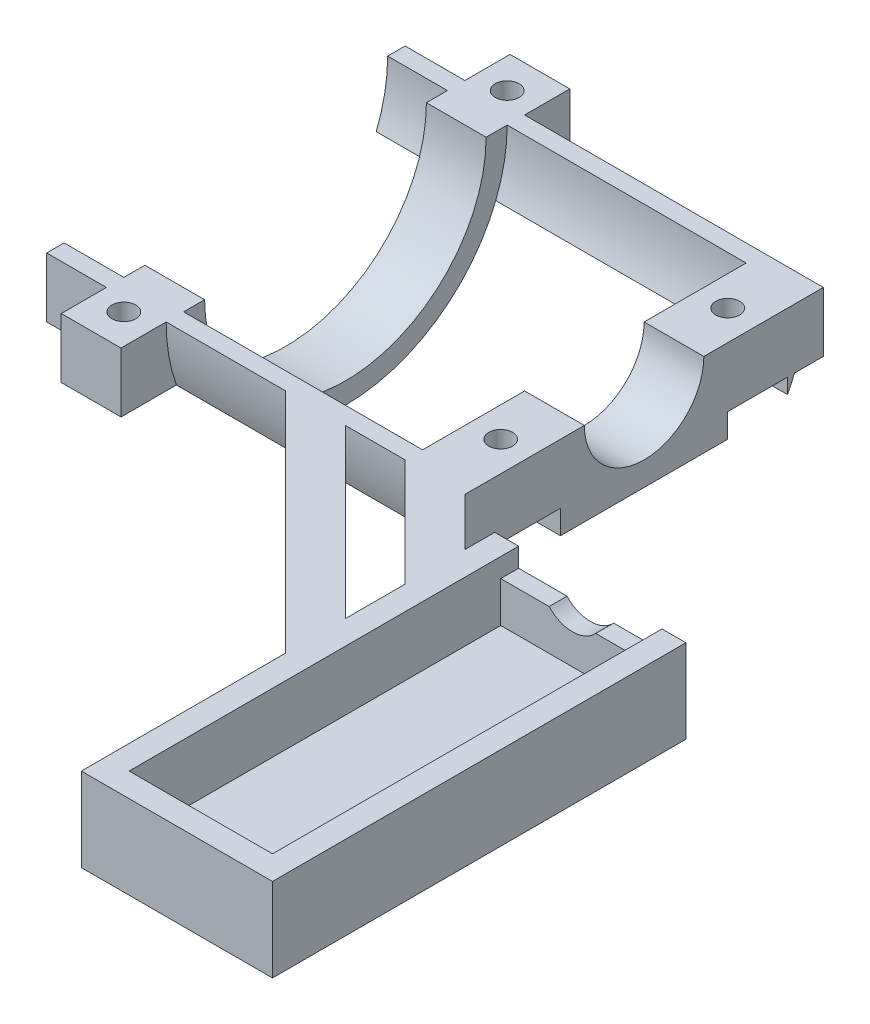
SolidWorks part; units mm, degrees
ref_plane "Front Plane" through (0, 0, 0) normal (0, 0, 1) x (1, 0, 0)
ref_plane "Top Plane" through (0, 0, 0) normal (0, 1, 0) x (1, 0, 0)
ref_plane "Right Plane" through (0, 0, 0) normal (1, 0, 0) x (0, 0, -1)
sketch "Sketch1" plane through (0, 0, 0) normal (0, 0, 1) x (1, 0, 0)
  line L0 (0, 0) -> (5, 0) construction
  line L1 (5, 0) -> (5, 1.76) construction
  line L2 (5, 1.76) -> (10, 1.76) construction
  line L3 (10, 1.76) -> (10, 0) construction
  line L4 (10, 0) -> (30, 0) construction
  line L5 (30, 0) -> (30, 8.54) construction
  line L6 (30, 8.54) -> (35, 8.54) construction
  line L7 (35, 8.54) -> (35, -3.4949) construction
  line L8 (35, -3.4949) -> (35, -5) construction
  line L9 (35, -5) -> (0, -5) construction
  line L10 (0, -5) -> (0, 0) construction
  dimension "D1" = 20
  dimension "D2" = 5
  dimension "D3" = 5
  dimension "D4" = 8.54
  dimension "D5" = 5
  dimension "D6" = 5
  dimension "D7" = 1.76
sketch "Sketch2" plane through (0, 0, 0) normal (1, 0, 0) x (0, 0, -1)
  line L0 (0, 0) -> (0, 13.54) construction
  line L1 (0, 13.54) -> (0, 1.76) construction
  line L2 (-15, 13.54) -> (-13.54, 13.54)
  line L3 (13.54, 13.54) -> (15, 13.54)
  line L4 (0, -1.46) -> (15, -1.46)
  line L5 (15, -1.46) -> (15, 13.54)
  line L6 (0, -1.46) -> (-15, -1.46)
  line L7 (-15, -1.46) -> (-15, 13.54)
  arc A0 (-13.54, 13.54) -> (13.54, 13.54) centre (0, 13.54) ccw
  dimension "D1" = 13.54
  dimension "D2" = 11.78
extrude "Boss-Extrude1" add sketch "Sketch2" along normal blind 35
sketch "Sketch3" plane through (35, 0, 0) normal (1, 0, 0) x (0, 0, -1)
  line L0 (-13.54, 13.54) -> (-5, 13.54)
  line L1 (5, 13.54) -> (13.54, 13.54)
  arc A0 (-5, 13.54) -> (5, 13.54) centre (0, 13.54) ccw
  arc A1 (-13.54, 13.54) -> (13.54, 13.54) centre (0, 13.54) ccw
extrude "Boss-Extrude2" add sketch "Sketch3" against normal blind 5
sketch "Sketch4" plane through (0, 0, 0) normal (-1, 0, 0) x (0, 0, 1)
  line L0 (-13.54, 13.54) -> (-11.78, 13.54)
  line L1 (11.78, 13.54) -> (13.54, 13.54)
  arc A0 (-13.54, 13.54) -> (13.54, 13.54) centre (0, 13.54) ccw
  arc A1 (-11.78, 13.54) -> (11.78, 13.54) centre (0, 13.54) ccw
  dimension "D1" = 23.56
extrude "Boss-Extrude3" add sketch "Sketch4" against normal blind 5 from offset 5 offset against normal yes
ref_plane "Plane1" through (35, 0, 0) normal (1, 0, 0) x (0, 0, -1)
sketch "Sketch5" plane through (35, 0, 0) normal (1, 0, 0) x (0, 0, -1)
  line L1 (0, 13.54) -> (0, -1.46) construction
  line L2 (-15, -1.46) -> (15, -1.46) construction
  line L3 (0, -1.46) -> (-15.28, -1.46) construction
  dimension "D1" = 15.28
sketch "Sketch6" plane through (0, 0, 0) normal (0, 0, 1) x (1, 0, 0)
  line L10 (33.5, 3.26) -> (31.5, 3.26)
  line L11 (33.5, -6.74) -> (45.5, -6.74)
  line L12 (33.5, -6.74) -> (33.5, 3.26)
  line L14 (45.5, -6.74) -> (45.5, 3.26)
  line L15 (33.5, -6.74) -> (45.5, 3.26) construction
  line L16 (33.5, 3.26) -> (45.5, -6.74) construction
  line L17 (31.5, -8.74) -> (47.5, -8.74)
  line L18 (31.5, -8.74) -> (31.5, 3.26)
  line L20 (47.5, -8.74) -> (47.5, 3.26)
  line L21 (31.5, -8.74) -> (47.5, 5.26) construction
  line L22 (31.5, 5.26) -> (47.5, -8.74) construction
  line L23 (45.5, 3.26) -> (47.5, 3.26)
  circle A0 centre (39.5, -1.74) radius 5.5 construction
  dimension "D1" = 11
  dimension "D7" = 14
  dimension "D8" = 16
sketch "Sketch7" plane through (0, 0, -15) normal (0, 0, -1) x (-1, 0, 0)
  line L0 (-35, 13.54) -> (-35, -1.74) construction
  line L1 (-35, -1.74) -> (-39.5, -1.74) construction
  line L2 (-33.5, -1.74) -> (-39.5, -1.74)
  line L3 (-39.5, -1.74) -> (-39.5, 4.26)
  arc A0 (-33.5, -1.74) -> (-39.5, 4.26) centre (-39.5, -1.74) ccw
  dimension "D1" = 15.28
  dimension "D2" = 4.5
extrude "Cut-Extrude1" cut sketch "Sketch7" against normal blind 31.1
sketch "Sketch10" plane through (0, 13.54, 0) normal (0, 1, 0) x (1, 0, 0)
  line L0 (5, -15) -> (5, -18.78)
  line L1 (35, -15) -> (0, -15) construction
  line L2 (5, -18.78) -> (10, -18.78)
  line L3 (10, -18.78) -> (10, -15)
  line L4 (10, -15) -> (5, -15)
  line L5 (32.5, 0) -> (15.1517, 0) construction
  line L6 (30, 0) -> (35, 0) construction
  line L7 (10, 0) -> (30, 0) construction
  line L8 (10, 15) -> (5, 15)
  line L9 (10, 18.78) -> (10, 15)
  line L10 (5, 18.78) -> (10, 18.78)
  line L11 (5, 15) -> (5, 18.78)
  dimension "D1" = 3.78
  dimension "D2" = 5
extrude "Boss-Extrude6" add sketch "Sketch10" against normal blind 5
sketch "Sketch11" plane through (0, 0, 0) normal (-1, 0, 0) x (0, 0, 1)
  line L0 (-15, 13.54) -> (-15, -1.46)
  line L1 (-15, -1.46) -> (15, -1.46)
  line L2 (15, -1.46) -> (15, 13.54)
  line L3 (13.54, 13.54) -> (15, 13.54) construction
  arc A1 (-15, 13.54) -> (15, 13.54) centre (0, 13.54) ccw
  line M7 (-15, -1.46) -> (15, -1.46)
  line M8 (15, -1.46) -> (15, 13.54)
  line M12 (-15, 13.54) -> (-15, -1.46)
extrude "Cut-Extrude4" cut sketch "Sketch11" against normal blind 20 from offset 10 contours A1 L1 M8 | A1 M12 M7 offset against normal yes
sketch "Sketch12" plane through (0, 13.54, 0) normal (0, 1, 0) x (1, 0, 0)
  circle A0 centre (7.5, -16.04) radius 1
  circle A1 centre (7.5, 16.04) radius 1
  circle A2 centre (32.5, -9.5) radius 1
  circle A3 centre (32.5, 9.5) radius 1
extrude "Cut-Extrude5" cut sketch "Sketch12" against normal blind 10
ref_plane "Plane2" through (0, 8.54, 0) normal (0, 1, 0) x (1, 0, 0)
sketch "Sketch13" plane through (0, 8.54, 0) normal (0, 1, 0) x (1, 0, 0)
  line L0 (32.5, 12) -> (35, 12)
  line L1 (35, 15) -> (35, 5) construction
  line L2 (32.5, 7) -> (35, 7)
  line L4 (32.5, -7) -> (35, -7)
  line L5 (35, 0) -> (35, -15.28) construction
  line L9 (35, 12) -> (35.7539, 12)
  line L10 (35.7539, 12) -> (35.7539, 7)
  line L11 (35.7539, 7) -> (35, 7)
  line L12 (35, -7) -> (35.7539, -7)
  line L13 (35.7539, -7) -> (35.7539, -12)
  line L15 (32.5, -12) -> (35.7539, -12)
  line L17 (30.1, -9.5) -> (30.1, -10.2)
  line L18 (30.1, -9.5) -> (30.1, -8.8)
  line L20 (30.1, 9.5) -> (30.1, 10.2)
  line L21 (30.1, 9.5) -> (30.1, 8.8)
  arc A1 (32.5, 12) -> (30.1, 10.2) centre (32.5, 9.5) ccw
  arc A4 (32.5, -7) -> (30.1, -8.8) centre (32.5, -9.5) ccw
  arc A5 (30.1, -10.2) -> (32.5, -12) centre (32.5, -9.5) ccw
  arc A6 (30.1, 8.8) -> (32.5, 7) centre (32.5, 9.5) ccw
extrude "Cut-Extrude11" cut sketch "Sketch13" against normal blind 2
sketch "Sketch14" plane through (0, 8.54, 0) normal (0, -1, 0) x (1, 0, 0)
  circle A0 centre (7.5, 16.04) radius 2.5
  circle A1 centre (7.5, -16.04) radius 2.5
extrude "Cut-Extrude12" cut sketch "Sketch14" along normal blind 2
ref_plane "Plane3" through (0, 0, 0) normal (0, 0, -1) x (-1, 0, 0)
sketch "Sketch15" plane through (0, 0, 0) normal (0, 0, -1) x (-1, 0, 0)
  line L0 (-42.1146, 19.7229) -> (-47.3533, 13.093) construction
  line L2 (-41.9143, 7.098) -> (-47.3533, 13.9874) construction
  line L5 (-47.0001, 13.54) -> (-37, 13.54) construction
  circle A1 centre (-47.0001, 13.54) radius 2
  dimension "D1" = 4
extrude "Boss-Extrude7" add sketch "Sketch15" against normal blind 5 from offset 2 separate body offset against normal yes
ref_plane "Plane4" through (47, 0, 0) normal (1, 0, 0) x (0, 0, -1)
sketch "Sketch16" plane through (47, 0, 0) normal (1, 0, 0) x (0, 0, -1)
  line L0 (0, 13.54) -> (-16, 13.54) construction
  line L1 (-5, 13.54) -> (-15, 13.54) construction
  line L2 (-16, 13.54) -> (-18, 13.54) construction
  line L3 (-18, 11.94) -> (-18, 8.54)
  line L4 (-18, 8.54) -> (-49.1, 8.54)
  line L5 (-18, 11.94) -> (-16.5, 11.94)
  line L6 (-16.5, 11.94) -> (-16.5, 6.54)
  line L7 (-16.5, 6.54) -> (-49.1, 6.54)
  line L8 (-49.1, 8.54) -> (-49.1, 6.54)
  point P10 (-18, 11.94)
  dimension "D1" = 16
  dimension "D2" = 2
  dimension "D3" = 5
  dimension "D4" = 31.1
  dimension "D5" = 1.6
  dimension "D6" = 1.5
  dimension "D7" = 5.4
extrude "Boss-Extrude8" add sketch "Sketch16" along normal mid plane 12 separate body
sketch "Sketch18" plane through (41, 0, 0) normal (-1, 0, 0) x (0, 0, 1)
  line L0 (16.5, 6.54) -> (16.5, 18.54)
  line L1 (16.5, 6.54) -> (49.1, 6.54)
  line L2 (16.5, 18.54) -> (49.1, 18.54)
  line L3 (49.1, 18.54) -> (49.1, 6.54)
  dimension "D1" = 12
extrude "Boss-Extrude9" add sketch "Sketch18" along normal blind 2
sketch "Sketch19" plane through (53, 0, 0) normal (1, 0, 0) x (0, 0, -1)
  line L0 (-16.5, 18.54) -> (-16.5, 6.54)
  line L1 (-16.5, 6.54) -> (-49.1, 6.54)
  line L2 (-49.1, 6.54) -> (-49.1, 18.54)
  line L3 (-49.1, 18.54) -> (-16.5, 18.54)
extrude "Boss-Extrude10" add sketch "Sketch19" along normal blind 2
sketch "Sketch20" plane through (35, 0, 0) normal (1, 0, 0) x (0, 0, -1)
  line L0 (15, 8.54) -> (12.583, 8.54)
  line L1 (15, 8.54) -> (15, -1.46)
  line L2 (15, -1.46) -> (-15, -1.46)
  line L3 (0, -1.46) -> (-15.28, -1.46) construction
  line L4 (-15, 2.2286) -> (-15, -1.46) construction
  line L5 (-15, -1.46) -> (-15, 8.54)
  line L6 (-15, 8.54) -> (-12.581, 8.54)
  arc A0 (-13.54, 13.54) -> (13.54, 13.54) centre (0, 13.54) ccw construction
  arc A1 (-12.581, 8.54) -> (12.583, 8.54) centre (0.001, 13.5396) ccw
extrude "Cut-Extrude13" cut sketch "Sketch20" against normal through all
sketch "Sketch21" plane through (0, 13.54, 0) normal (0, 1, 0) x (1, 0, 0)
  line L0 (35, -15) -> (35, -20.476) construction
  line L1 (35, 0) -> (35, -15.28) construction
  line L2 (35, -15) -> (30, -15) construction
  line L3 (35, -6.2213) -> (35, 6.2213) construction
  line L4 (35, -15) -> (37.4061, -17.4061) construction
  line L5 (35, -15) -> (39, -19)
  line L6 (39, -49.1) -> (39, -16.5) construction
  line L7 (35, -15) -> (30, -15)
  line L8 (30, -15) -> (39, -24)
  line L9 (39, -19) -> (39, -24)
  line L10 (30, -15) -> (25, -15) construction
  line L11 (30, -15) -> (10, -15) construction
  line L12 (25, -15) -> (39, -29)
  line L14 (20, -15) -> (39, -34)
  line L15 (39, -29) -> (39, -34)
  line L16 (20, -15) -> (19.1421, -14.1421)
  line L17 (30, -14.1421) -> (10, -14.1421) construction
  line L18 (25, -15) -> (24.1421, -14.1421)
  line L19 (24.1421, -14.1421) -> (19.1421, -14.1421)
  dimension "D1" = 45
  dimension "D2" = 5
extrude "Boss-Extrude12" add sketch "Sketch21" against normal up to vertex
sketch "Sketch22" plane through (0, 13.54, 0) normal (0, 1, 0) x (1, 0, 0)
  line L0 (39, -16.5) -> (55, -16.5)
  line L1 (55, -16.5) -> (55, -49.1) construction
  line L2 (55, -16.5) -> (55, -49.1)
  line L3 (55, -49.1) -> (39, -49.1)
  line L4 (39, -49.1) -> (39, -16.5) construction
  line L5 (39, -49.1) -> (39, -16.5)
extrude "Cut-Extrude14" cut sketch "Sketch22" along normal up to vertex
sketch "Sketch23" plane through (0, 0, 2) normal (0, 0, -1) x (-1, 0, 0)
  circle A0 centre (-47.0001, 13.54) radius 2
extrude "Cut-Extrude15" cut sketch "Sketch23" against normal blind 5
sketch "Sketch24" plane through (35, 0, 0) normal (1, 0, 0) x (0, 0, -1)
  line L1 (-11.5882, 6.54) -> (11.5901, 6.54)
  arc A0 (-11.5877, 6.54) -> (11.5877, 6.54) centre (0, 13.54) ccw
extrude "Cut-Extrude-Thin1" cut sketch "Sketch24" against normal blind 5 thin
sketch "Sketch25" plane through (0, 0, 18) normal (0, 0, 1) x (1, 0, 0)
  line L0 (47, -6.2213) -> (47, 6.2213) construction
  line L1 (45.0479, 11.94) -> (48.9521, 11.94)
  line L2 (53, 11.94) -> (41, 11.94) construction
  arc A0 (45.0479, 11.94) -> (48.9521, 11.94) centre (47, 13.7367) ccw
extrude "Cut-Extrude16" cut sketch "Sketch25" against normal blind 5
sketch "Sketch26" plane through (0, 0, 49.1) normal (0, 0, 1) x (1, 0, 0)
  line L0 (39, 13.54) -> (39, 6.54)
  line L1 (39, 6.54) -> (55, 6.54)
  line L2 (55, 6.54) -> (55, 13.54)
  line L3 (55, 13.54) -> (55, 6.54) construction
  line L4 (55, 13.54) -> (39, 13.54)
extrude "Boss-Extrude13" add sketch "Sketch26" along normal blind 2
